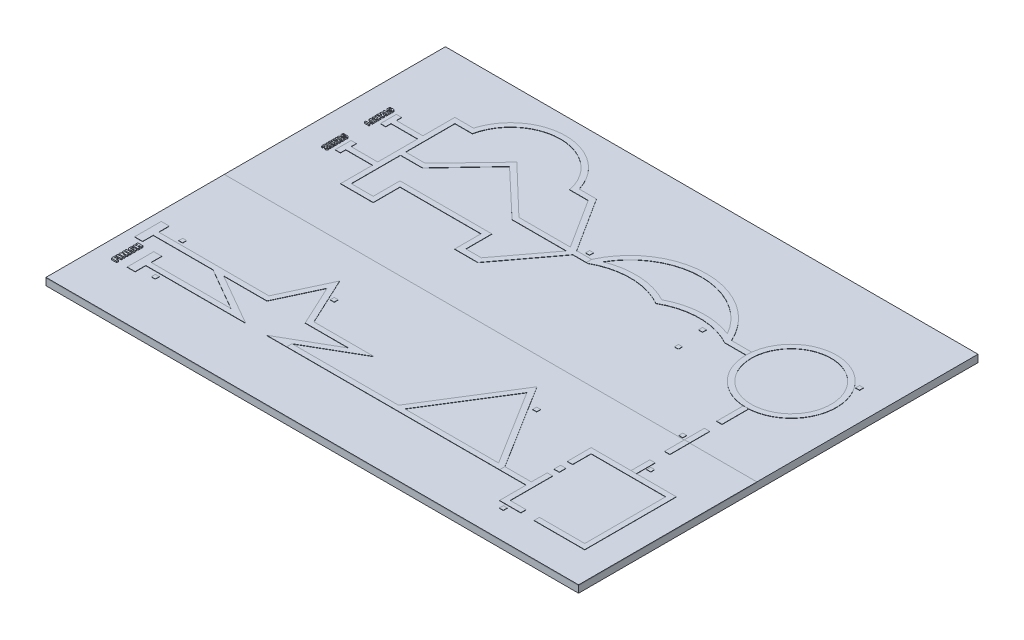
SolidWorks part; units mm, degrees
ref_plane "Front Plane" through (0, 0, 0) normal (0, 0, 1) x (1, 0, 0)
ref_plane "Top Plane" through (0, 0, 0) normal (0, 1, 0) x (1, 0, 0)
ref_plane "Right Plane" through (0, 0, 0) normal (1, 0, 0) x (0, 0, -1)
sketch "Sketch1" plane through (0, 0, 0) normal (0, 1, 0) x (1, 0, 0)
  line L1 (-2732.8747, 1805.1603) -> (1267.1253, 1805.1603)
  line L2 (-2732.8747, 1805.1603) -> (-2732.8747, -1194.8397)
  line L3 (-2732.8747, -1194.8397) -> (1267.1253, -1194.8397)
  line L4 (1267.1253, 1805.1603) -> (1267.1253, -1194.8397)
  dimension "D1" = 3000
  dimension "D2" = 4000
extrude "Boss-Extrude1" add sketch "Sketch1" along normal blind 50
sketch "Sketch2" plane through (0, 50, 0) normal (0, 1, 0) x (1, 0, 0)
  line L0 (1267.1253, -1194.8397) -> (1267.1253, 1805.1603) construction
  line L1 (-2732.8747, 1805.1603) -> (1267.1253, 1805.1603)
  line L2 (-2732.8747, 1805.1603) -> (-2732.8747, 305.1603)
  line L3 (-2732.8747, 305.1603) -> (1267.1253, 305.1603)
  line L4 (1267.1253, 1805.1603) -> (1267.1253, 305.1603)
extrude "Boss-Extrude2" add sketch "Sketch2" along normal blind 5 separate body
sketch "Sketch3" plane through (0, 50, 0) normal (0, 1, 0) x (1, 0, 0)
  line L1 (-2732.8747, 305.1603) -> (1267.1253, 305.1603)
  line L2 (-2732.8747, 305.1603) -> (-2732.8747, -1194.8397)
  line L3 (-2732.8747, -1194.8397) -> (1267.1253, -1194.8397)
  line L4 (1267.1253, 305.1603) -> (1267.1253, -1194.8397)
sketch "Sketch4" plane through (0, 55, 0) normal (0, 1, 0) x (1, 0, 0)
  line L0 (-2475.3799, 1179.1062) -> (-2475.3799, 1059.1062)
  line L1 (-2475.3799, 719.1062) -> (-2435.3799, 719.1062)
  line L2 (-2435.3799, 719.1062) -> (-2435.3799, 759.1062)
  line L3 (-2435.3799, 759.1062) -> (-2234.2178, 759.1062)
  line L4 (-900.183, 929.1062) -> (-798.4947, 929.1062)
  line L5 (-2235.3934, 799.1062) -> (-2435.3934, 799.1062)
  line L6 (-2475.3799, 1059.1062) -> (-2435.3934, 1059.1062)
  line L7 (-2435.3934, 1099.1062) -> (-2235.3934, 1099.1062)
  line L8 (-798.4947, 929.1062) -> (-798.4947, 969.1062)
  line L9 (-2236.1347, 1139.1062) -> (-2435.3799, 1139.1062)
  line L10 (-2435.3799, 1139.1062) -> (-2435.3799, 1179.1062)
  line L11 (-2435.3799, 1179.1062) -> (-2475.3799, 1179.1062)
  line L12 (-2236.1347, 1139.1062) -> (-2236.1347, 1379.1062)
  line L13 (-798.4947, 969.1062) -> (-911.1971, 969.1062)
  line L14 (-2195.3934, 1339.1062) -> (-2195.3934, 969.1062)
  line L15 (-1195.0841, 1339.8246) -> (-1333.8478, 1339.8246)
  line L16 (-2234.2178, 519.1062) -> (-2234.2178, 759.1062)
  line L17 (-2235.3934, 799.1062) -> (-2235.3934, 1099.1062)
  line L18 (-2195.3934, 1339.1062) -> (-2064.4012, 1339.1062)
  line L19 (-2435.3934, 1059.1062) -> (-2435.3934, 1099.1062)
  line L20 (-2096.1347, 1379.1062) -> (-2236.1347, 1379.1062)
  line L21 (-1711.2389, 1265.0533) -> (-1356.2378, 929.1062)
  line L22 (-2194.2178, 559.1062) -> (-2029.1547, 559.1062)
  line L23 (-1356.2378, 929.1062) -> (-948.5451, 929.1062)
  line L24 (-1711.2389, 1265.0533) -> (-2029.1547, 929.1062)
  line L25 (-2194.2178, 929.1062) -> (-2194.2178, 559.1062)
  line L26 (-2029.1547, 559.1062) -> (-2029.1547, 760.2076)
  line L27 (-1712.1546, 1320.861) -> (-2049.0821, 969.1062)
  line L28 (-1205.7131, 521.9307) -> (-900.183, 929.1062)
  line L29 (-2475.3799, 719.1062) -> (-2475.3799, 839.1062)
  line L30 (-1712.1546, 1320.861) -> (-1344.9199, 969.1062)
  line L31 (-2029.1547, 760.2076) -> (-1338.9208, 760.2076)
  line L32 (-1338.9208, 760.2076) -> (-1338.9208, 565.0279)
  line L33 (-2194.2178, 929.1062) -> (-2029.1547, 929.1062)
  line L34 (-1195.0841, 1339.8246) -> (-958.6235, 969.1062)
  line L35 (-2049.0821, 969.1062) -> (-2195.3934, 969.1062)
  line L36 (-1989.1547, 519.1062) -> (-1989.1547, 720.2076)
  line L37 (-1152.3914, 929.1062) -> (-1152.3914, 969.1062)
  line L38 (-2029.1547, 929.1062) -> (-2031.3176, 927.2496)
  line L39 (-1989.1547, 720.2076) -> (-1380.5466, 720.2076)
  line L40 (-1344.9199, 969.1062) -> (-958.6235, 969.1062)
  line L41 (-1380.5466, 720.2076) -> (-1380.5466, 521.9307)
  line L42 (-1989.1547, 519.1062) -> (-2234.2178, 519.1062)
  line L43 (-2475.3799, 839.1062) -> (-2435.3934, 839.1062)
  line L44 (-1173.1361, 1379.8246) -> (-911.1971, 969.1062)
  line L45 (-2435.3934, 839.1062) -> (-2435.3934, 799.1062)
  line L47 (-948.5451, 929.1062) -> (-1223.0573, 565.0279)
  line L48 (-1223.0573, 565.0279) -> (-1338.9208, 565.0279)
  line L51 (-1173.1361, 1379.8246) -> (-1303.2668, 1379.8246)
  line L52 (-1380.5466, 521.9307) -> (-1205.7131, 521.9307)
  arc A0 (-2096.1347, 1379.1062) -> (-1303.2668, 1379.8246) centre (-1699.5945, 1262.1991) cw
  arc A1 (-2064.4012, 1339.1062) -> (-1333.8478, 1339.8246) centre (-1699.0486, 1262.2313) cw
extrude "Boss-Extrude4" add sketch "Sketch4" along normal blind 2 separate body
sketch "Sketch5" plane through (0, 55, 0) normal (0, 1, 0) x (1, 0, 0)
  line L0 (80.6369, 741.8927) -> (80.6369, 711.8927)
  line L1 (80.6369, 711.8927) -> (110.6369, 711.8927)
  line L2 (110.6369, 711.8927) -> (110.6369, 741.8927)
  line L3 (110.6369, 741.8927) -> (80.6369, 741.8927)
extrude "Boss-Extrude6" add sketch "Sketch5" along normal blind 2 separate body
sketch "Sketch7" plane through (0, 55, 0) normal (0, 1, 0) x (1, 0, 0)
  circle A0 centre (743.3692, 926.2065) radius 340
  circle A1 centre (743.3692, 926.2065) radius 300
extrude "Boss-Extrude8" add sketch "Sketch7" along normal blind 2 separate body
sketch "Sketch8" plane through (0, 50, 0) normal (0, 1, 0) x (1, 0, 0)
  line L0 (1267.1253, 305.1603) -> (1267.1253, -1194.8397) construction
  line L1 (-2732.8747, 305.1603) -> (1267.1253, 305.1603)
  line L2 (-2732.8747, 305.1603) -> (-2732.8747, 144.3403)
  line L3 (-2732.8747, 144.3403) -> (1267.1253, 144.3403)
  line L4 (1267.1253, 305.1603) -> (1267.1253, 144.3403)
  dimension "D1" = 160.82
extrude "Boss-Extrude9" add sketch "Sketch8" along normal blind 5
sketch "Sketch9" plane through (0, 50, 0) normal (0, 1, 0) x (1, 0, 0)
  line L1 (-2732.8747, 144.3403) -> (1267.1253, 144.3403)
  line L2 (-2732.8747, 144.3403) -> (-2732.8747, -1194.8397)
  line L3 (-2732.8747, -1194.8397) -> (1267.1253, -1194.8397)
  line L4 (1267.1253, 144.3403) -> (1267.1253, -1194.8397)
extrude "Boss-Extrude10" add sketch "Sketch9" along normal blind 5 separate body
sketch "Sketch11" plane through (0, 55, 0) normal (0, 1, 0) x (1, 0, 0)
  line L0 (723.369, 586.7953) -> (763.4279, 586.7987)
  line L1 (763.4279, 586.7987) -> (763.4279, 386.2065)
  line L2 (763.4279, 386.2065) -> (723.369, 386.2065)
  line L3 (723.369, 386.2065) -> (723.369, 586.7953)
  line L4 (763.4279, 294.3403) -> (763.4279, 144.3403)
  line L5 (-2732.8747, 144.3403) -> (1267.1253, 144.3403) construction
  line L6 (763.4279, 144.3403) -> (723.369, 144.3403)
  line L7 (723.369, 144.3403) -> (723.369, 294.3403)
  line L8 (723.369, 294.3403) -> (763.4279, 294.3403)
  circle A2 centre (743.3692, 926.2065) radius 340 construction
extrude "Boss-Extrude11" add sketch "Sketch11" along normal blind 2 separate body
sketch "Sketch12" plane through (0, 55, 0) normal (0, 1, 0) x (1, 0, 0)
  line L0 (723.369, 144.3403) -> (723.369, -5.6597)
  line L1 (723.369, -5.6597) -> (763.4279, -5.6597)
  line L2 (763.4279, -5.6597) -> (763.4279, 144.3403)
  line L3 (-2732.8747, 144.3403) -> (1267.1253, 144.3403) construction
  line L4 (723.369, 144.3403) -> (763.4279, 144.3403) construction
  line L5 (763.4279, 144.3403) -> (723.369, 144.3403)
  line L6 (723.369, -5.6597) -> (723.369, 144.3403)
  line L7 (763.4279, -115.6834) -> (763.4279, -265.6834)
  line L8 (763.4279, -265.6834) -> (723.369, -265.6834)
  line L9 (723.369, -265.6834) -> (723.369, -115.6834)
  line L10 (723.369, -115.6834) -> (763.4279, -115.6834)
  line L11 (723.369, -115.6834) -> (723.369, -265.6834)
  line M4 (1267.1253, 144.3403) -> (-2732.8747, 144.3403)
extrude "Boss-Extrude12" add sketch "Sketch12" along normal blind 2 separate body contours L10 L9 L8 L7 | L1 L2 L0 M4
sketch "Sketch13" plane through (0, 55, 0) normal (0, 1, 0) x (1, 0, 0)
  line L0 (743.5211, -256.9587) -> (423.5211, -256.9587)
  line L1 (423.5211, -436.1801) -> (463.5211, -436.1801)
  line L2 (463.5211, -436.1801) -> (463.5211, -296.9587)
  line L3 (1063.2653, -944.7868) -> (683.2653, -944.7868)
  line L4 (743.5211, -256.9587) -> (1063.2653, -256.9587)
  line L5 (423.4305, -744.7868) -> (223.4305, -744.7868)
  line L6 (683.2653, -944.7868) -> (683.2653, -904.7868)
  line L7 (1063.2653, -256.9587) -> (1063.2653, -944.7868)
  line L8 (223.4305, -744.7868) -> (223.4305, -704.7868)
  line L9 (223.4305, -704.7868) -> (421.9684, -704.7868)
  line L10 (683.2653, -904.7868) -> (1023.5211, -904.7868)
  line L11 (1023.5211, -596.4996) -> (1023.5211, -296.9587)
  line L12 (1023.5211, -296.9587) -> (743.5211, -296.9587)
  line L13 (421.9684, -704.7868) -> (423.5211, -586.1801)
  line L14 (743.5211, -296.9587) -> (463.5211, -296.9587)
  line L16 (1023.5211, -904.7868) -> (1023.5211, -596.4996)
  line L17 (423.5211, -436.1801) -> (423.5211, -256.9587)
  line L18 (423.5211, -586.1801) -> (463.5211, -586.1801)
  line L19 (423.4305, -744.7868) -> (423.4305, -944.7868)
  line L20 (423.4305, -944.7868) -> (583.2653, -944.7868)
  line L21 (583.2653, -944.7868) -> (583.2653, -904.7868)
  line L22 (463.4305, -904.7242) -> (583.2653, -904.7868)
  line L23 (463.5211, -586.1801) -> (463.4305, -904.7242)
extrude "Boss-Extrude14" add sketch "Sketch13" along normal blind 2 separate body
sketch "Sketch15" plane through (0, 55, 0) normal (0, 1, 0) x (1, 0, 0)
  line L0 (223.4326, -744.79) -> (223.4326, -704.7852)
  line L1 (176.2991, -704.7852) -> (-175.2717, -140.5883)
  line L2 (223.4326, -704.7852) -> (-175.2194, -65.0329)
  line L3 (223.4326, -704.7852) -> (-575.0646, -704.7852)
  line L4 (-175.2194, -65.0329) -> (-575.0646, -704.7852)
  line L5 (223.4326, -744.79) -> (-1375.2194, -744.79)
  line L6 (-1375.2194, -744.79) -> (-1375.2194, -704.7852)
  line L7 (-341.2995, -406.2328) -> (-175.2717, -140.5883)
  line L8 (-341.2995, -406.2328) -> (-527.8947, -704.7852)
  line L9 (-1375.2194, -704.7852) -> (-575.0646, -704.7852)
extrude "Boss-Extrude17" add sketch "Sketch15" along normal blind 2 separate body contours L8 L7 L1 L3 L2 L4 | L9 L6 L5 L0 L3
sketch "Sketch16" plane through (0, 55, 0) normal (0, 1, 0) x (1, 0, 0)
  line L0 (-985.2544, -480.225) -> (-1435.2544, -480.225)
  line L1 (-1435.2544, -480.225) -> (-1604.3017, -117.7019)
  line L2 (-1375.2194, -704.7852) -> (-1375.2194, -744.7852)
  line L3 (-1375.2194, -704.7852) -> (-985.2544, -480.225)
  line L4 (-1833.384, -704.7852) -> (-2152.8018, -520.225)
  line L5 (-2223.675, -479.2744) -> (-1773.349, -480.225)
  line L6 (-1773.349, -480.225) -> (-1604.3017, -117.7019)
  line L7 (-1833.384, -704.7852) -> (-2433.384, -704.7852)
  line L8 (-2223.675, -479.2744) -> (-2601.9137, -479.2744)
  line L9 (-2433.384, -744.7852) -> (-1683.7644, -744.7852)
  line L10 (-2433.384, -704.7852) -> (-2433.384, -624.7852)
  line L11 (-2073.8931, -520.1308) -> (-1683.7644, -744.7852)
  line L12 (-1134.874, -520.225) -> (-1524.839, -744.7852)
  line L13 (-2073.8931, -520.1308) -> (-1747.8223, -520.1308)
  line L14 (-1134.874, -520.225) -> (-1460.7372, -520.225)
  line L15 (-1524.839, -744.7852) -> (-1375.2194, -744.7852)
  line L16 (-2433.384, -624.7852) -> (-2493.384, -624.7852)
  line L17 (-1604.3017, -212.35) -> (-1747.8223, -520.1308)
  line L18 (-1604.3017, -212.35) -> (-1460.7372, -520.225)
  line L19 (-2493.384, -624.7852) -> (-2493.384, -824.7852)
  line L20 (-2493.384, -824.7852) -> (-2433.384, -824.7852)
  line L21 (-2433.384, -824.7852) -> (-2433.384, -744.7852)
  line L22 (-2601.9137, -479.2744) -> (-2601.9137, -400.225)
  line L23 (-2601.9137, -400.225) -> (-2661.9137, -400.225)
  line L24 (-2661.9137, -400.225) -> (-2661.9137, -600.225)
  line L25 (-2661.9137, -600.225) -> (-2601.9137, -600.225)
  line L26 (-2601.9137, -600.225) -> (-2601.9137, -520.225)
  line L27 (-2601.9137, -520.225) -> (-2152.8018, -520.225)
extrude "Boss-Extrude19" add sketch "Sketch16" along normal blind 2 separate body
sketch "Sketch17" plane through (0, 55, 0) normal (0, 1, 0) x (1, 0, 0)
  line L0 (-864.0687, 1019.1062) -> (-834.0687, 1019.1062)
  line L1 (-834.0687, 1019.1062) -> (-834.0687, 989.1062)
  line L2 (-834.0687, 989.1062) -> (-864.0687, 989.1062)
  line L3 (-864.0687, 989.1062) -> (-864.0687, 1019.1062)
  line L9 (1028.0421, 1154.627) -> (1058.0421, 1154.627)
  line L11 (1058.0421, 1154.627) -> (1058.0421, 1124.627)
  line L12 (1058.0421, 1124.627) -> (1028.0421, 1124.627)
  line L13 (1028.0421, 1124.627) -> (1028.0421, 1154.627)
  line L14 (673.369, 181.4915) -> (703.369, 181.4915)
  line L15 (703.369, 181.4915) -> (703.369, 151.4915)
  line L16 (703.369, 151.4915) -> (673.369, 151.4915)
  line L17 (673.369, 151.4915) -> (673.369, 181.4915)
  line L18 (775.5218, -161.21) -> (805.5218, -161.21)
  line L26 (805.5218, -161.21) -> (805.5218, -191.21)
  line L27 (805.5218, -191.21) -> (775.5218, -191.21)
  line L28 (775.5218, -191.21) -> (775.5218, -161.21)
  line L29 (471.6247, -964.7868) -> (501.6247, -964.7868)
  line L32 (501.6247, -964.7868) -> (501.6247, -994.7868)
  line L33 (501.6247, -994.7868) -> (471.6247, -994.7868)
  line L34 (471.6247, -994.7868) -> (471.6247, -964.7868)
  line L35 (-44.006, -198.2776) -> (-14.006, -198.2776)
  line L38 (-14.006, -198.2776) -> (-14.006, -228.2776)
  line L39 (-14.006, -228.2776) -> (-44.006, -228.2776)
  line L40 (-44.006, -228.2776) -> (-44.006, -198.2776)
  line L41 (-2339.7533, -766.9172) -> (-2309.7533, -766.9172)
  line L43 (-2309.7533, -766.9172) -> (-2309.7533, -796.9172)
  line L44 (-2309.7533, -796.9172) -> (-2339.7533, -796.9172)
  line L45 (-2339.7533, -796.9172) -> (-2339.7533, -766.9172)
  line L46 (-2472.0049, -429.2744) -> (-2442.0049, -429.2744)
  line L47 (-2442.0049, -429.2744) -> (-2442.0049, -459.2744)
  line L48 (-2442.0049, -459.2744) -> (-2472.0049, -459.2744)
  line L49 (-2472.0049, -459.2744) -> (-2472.0049, -429.2744)
  line L50 (-1517.8402, -245.2292) -> (-1487.8402, -245.2292)
  line L52 (-1487.8402, -245.2292) -> (-1487.8402, -275.2292)
  line L53 (-1487.8402, -275.2292) -> (-1517.8402, -275.2292)
  line L54 (-1517.8402, -275.2292) -> (-1517.8402, -245.2292)
extrude "Boss-Extrude20" add sketch "Sketch17" along normal blind 2 separate body
sketch "Sketch19" plane through (0, 55, 0) normal (0, 1, 0) x (1, 0, 0)
  line L0 (-798.4292, 969.1079) -> (-798.4292, 929.1079)
  line L1 (405.8037, 966.8209) -> (403.3702, 927.0376)
  line L3 (-798.4292, 929.1079) -> (-787.8631, 929.1079)
  line L4 (254.2027, 966.8209) -> (405.8037, 966.8209)
  line L6 (403.3702, 927.0376) -> (254.0246, 927.0376)
  line L7 (254.0246, 927.0376) -> (243.4585, 927.0569)
  arc A0 (-271.2683, 924.6399) -> (243.4585, 927.0569) centre (-11.7515, 467.2466) cw
  arc A1 (-271.8561, 969.8142) -> (254.2027, 966.8209) centre (-11.6352, 474.7417) cw
  arc A2 (-271.8561, 969.8142) -> (-798.4292, 969.1079) centre (-534.4772, 473.3386) ccw
  arc A3 (-271.2683, 924.6399) -> (-787.8631, 929.1079) centre (-533.5401, 467.3534) ccw
  arc A4 (-798.4292, 969.1079) -> (254.2027, 966.8209) centre (-272.6304, 729.9374) cw
  arc A5 (-739.9334, 996.0676) -> (195.0838, 994.4329) centre (-272.889, 729.7664) cw
  circle A6 centre (743.3692, 926.2065) radius 340 construction
extrude "Boss-Extrude21" add sketch "Sketch19" along normal blind 2 separate body contours A2 A5 A1 A4 | A3 A0 L7 L6 L1 L4 A1 A2 L0 L3
sketch "Sketch21" plane through (0, 55, 0) normal (0, 1, 0) x (1, 0, 0)
  line L0 (60.806, 942.4671) -> (60.806, 912.4671)
  line L1 (60.806, 912.4671) -> (90.806, 912.4671)
  line L2 (90.806, 912.4671) -> (90.806, 942.4671)
  line L3 (90.806, 942.4671) -> (60.806, 942.4671)
extrude "Boss-Extrude22" add sketch "Sketch21" along normal blind 2 separate body
sketch "Sketch22" plane through (0, 0, 0) normal (0, 0, 1) x (1, 0, 0)
  circle A0 centre (23.401, 40.5328) radius 5.6519
sketch "Sketch23" plane through (0, 55, 0) normal (0, 1, 0) x (1, 0, 0)
  circle A0 centre (23.401, 40.5328) radius 5.6519
sketch "Sketch26" plane through (0, 55, 0) normal (0, 1, 0) x (1, 0, 0)
  line L1 (423.5211, -486.1801) -> (463.5211, -486.1801)
  line L2 (463.5211, -486.1801) -> (463.5211, -536.1801)
  line L3 (463.5211, -536.1801) -> (423.5211, -536.1801)
  line L5 (423.5211, -486.1801) -> (423.5211, -536.1801)
extrude "Boss-Extrude23" add sketch "Sketch26" along normal blind 2 separate body
sketch "Sketch28" plane through (0, 55, 0) normal (0, 1, 0) x (1, 0, 0)
  line L0 (-2543.0446, 851.5281) -> (-2543.0446, 692.5445) construction
  text T0 "START2" font "Swis721 BlkCn BT" height 40
extrude "Boss-Extrude26" add sketch "Sketch28" along normal blind 10 separate body
sketch "Sketch29" plane through (0, 55, 0) normal (0, 1, 0) x (1, 0, 0)
  line L0 (-2538.4077, 1196.8776) -> (-2538.4077, 1017.4913) construction
  text T0 "START1" font "Swis721 Blk BT" height 35
extrude "Boss-Extrude27" add sketch "Sketch29" along normal blind 10 separate body
sketch "Sketch30" plane through (0, 55, 0) normal (0, 1, 0) x (1, 0, 0)
  line L0 (-2562.9257, -609.965) -> (-2562.9257, -859.5849) construction
  text T0 "FINISH" font "Swis721 Blk BT" height 40
extrude "Boss-Extrude28" add sketch "Sketch30" along normal blind 10 separate body
